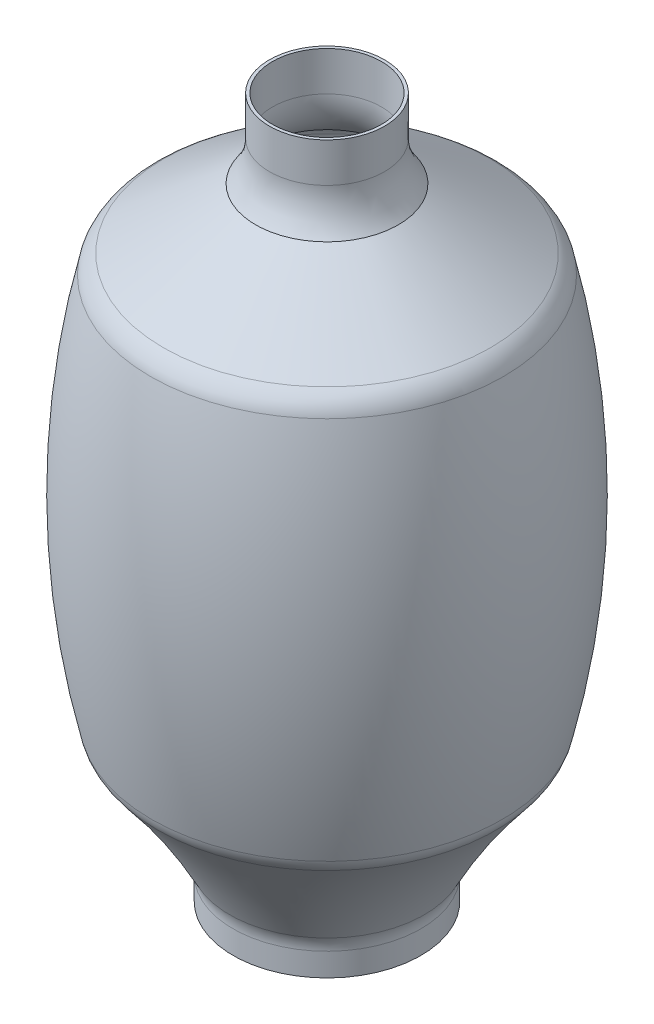
SolidWorks part; units mm, degrees
ref_plane "Alzado" through (0, 0, 0) normal (0, 0, 1) x (1, 0, 0)
ref_plane "Planta" through (0, 0, 0) normal (0, 1, 0) x (1, 0, 0)
ref_plane "Vista lateral" through (0, 0, 0) normal (1, 0, 0) x (0, 0, -1)
sketch "Croquis1" plane through (0, 0, 0) normal (0, 0, 1) x (1, 0, 0)
  line L1 (57.3, 0) -> (57.3, 133) construction
  line L3 (57.3, 133) -> (57.3, 181)
  line L4 (57.3, 0) -> (57.3, 133)
  line L5 (57.3, 0) -> (57.3, -50)
  line L6 (57.3, -50) -> (26.3, -50)
  line L7 (57.3, 181) -> (38.3, 181)
  line L8 (38.3, 181) -> (38.3, 168)
  line L9 (0, 133) -> (33.7403, 155.0973)
  line L10 (26.3, -50) -> (26.3, -40)
  arc A0 (0, 133) -> (0, 0) centre (268.8991, 66.5) ccw
  arc A1 (33.7403, 155.0973) -> (38.3, 168) centre (18.9229, 167.5907) ccw
  arc A2 (0, 0) -> (26.3, -40) centre (-149.1889, -126.7378) cw
  dimension "D5" = 277
  dimension "D1" = 57.3
  dimension "D2" = 48
  dimension "D4" = 19
  dimension "D6" = 13
  dimension "D3" = 50
  dimension "D7" = 31
  dimension "D8" = 10
revolve "Revolución2" add sketch "Croquis1" angle 360 about L4
fillet "Redondeo1" radius 10 1 edges at (57.3, 133, -57.3)
fillet "Redondeo2" radius 10 2 edges at (57.3, -40, -31) (57.3, 0, -57.3)
shell "Vaciado1" thickness 1
